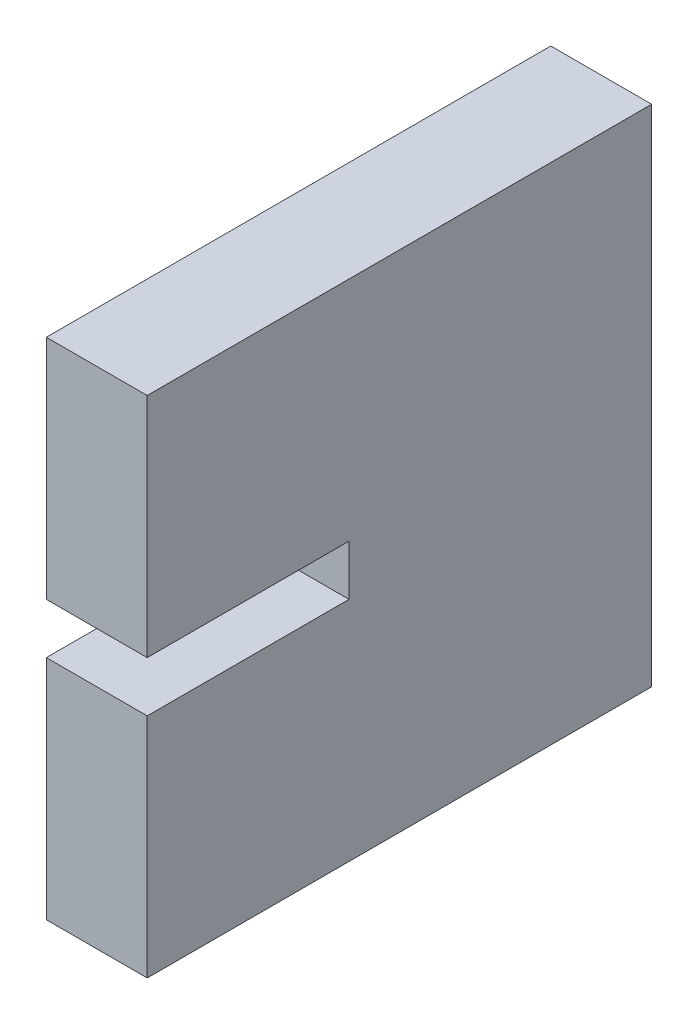
SolidWorks part; units mm, degrees
ref_plane "Front Plane" through (0, 0, 0) normal (0, 0, 1) x (1, 0, 0)
ref_plane "Top Plane" through (0, 0, 0) normal (0, 1, 0) x (1, 0, 0)
ref_plane "Right Plane" through (0, 0, 0) normal (1, 0, 0) x (0, 0, -1)
sketch "Sketch1" plane through (0, 0, 0) normal (1, 0, 0) x (0, 0, -1)
  line L0 (-50, 5) -> (-10, 5)
  line L1 (-50, 50) -> (50, 50)
  line L2 (-50, 50) -> (-50, 5)
  line L3 (-50, -50) -> (50, -50)
  line L4 (50, 50) -> (50, -50)
  line L5 (-50, 50) -> (50, -50) construction
  line L6 (-50, -50) -> (50, 50) construction
  line L7 (-10, 5) -> (-10, -5)
  line L8 (-10, -5) -> (-50, -5)
  line L9 (-50, -5) -> (-50, -50)
  point P1 (0, 0)
  point P8 (-10, 0)
  dimension "D1" = 10
  dimension "D2" = 60
  dimension "D3" = 100
  dimension "D4" = 100
extrude "Boss-Extrude1" add sketch "Sketch1" along normal blind 20 contours L0 L7 L8 L9 L3 L4 L1 L2
